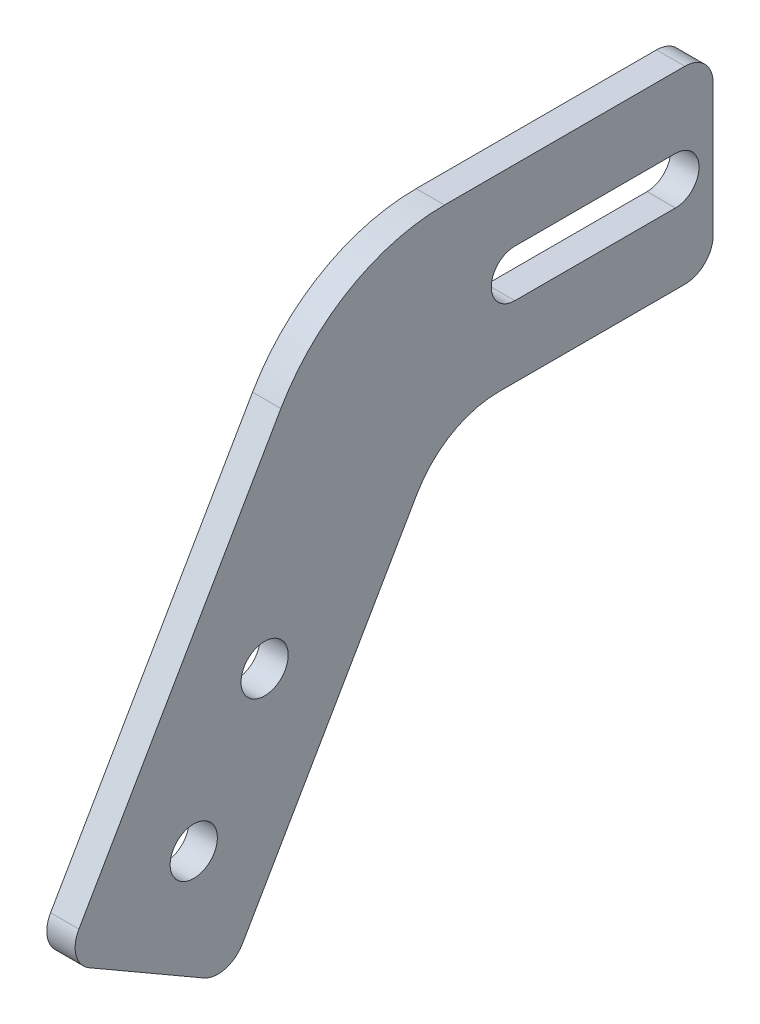
SolidWorks part; units mm, degrees
material "Thornel VCB-20 Carbon Cloth"
ref_plane "Front Plane" through (0, 0, 0) normal (0, 0, 1) x (1, 0, 0)
ref_plane "Top Plane" through (0, 0, 0) normal (0, 1, 0) x (1, 0, 0)
ref_plane "Right Plane" through (0, 0, 0) normal (1, 0, 0) x (0, 0, -1)
sketch "Sketch1" plane through (0, 0, 0) normal (1, 0, 0) x (0, 0, -1)
  line L7 (0, 0) -> (54.8406, 0) construction
  line L8 (0, 0) -> (-20, -34.641) construction
  line L9 (17.3205, 0) -> (40, 0)
  line L10 (40, 0) -> (40, 20)
  line L11 (40, 20) -> (11.547, 20)
  line L12 (-5.7735, 10) -> (-28.6603, -29.641)
  line L13 (8.6603, -5) -> (-11.3397, -39.641)
  line L14 (-8.6603, 5) -> (-28.6603, -29.641) construction
  line L15 (8.6603, -5) -> (-11.3397, -39.641) construction
  line L16 (0, 0) -> (19.0643, -11.0068) construction
  line L17 (-28.6603, -29.641) -> (-11.3397, -39.641)
  line L18 (40, 10) -> (-19.6071, 10) construction
  line L19 (0, 0) -> (0, 39.1739) construction
  line L20 (19, 12.5) -> (36, 12.5)
  line L21 (36, 7.5) -> (19, 7.5)
  arc A0 (8.6603, -5) -> (17.3205, 0) centre (17.3205, -10) cw
  arc A1 (-5.7735, 10) -> (11.547, 20) centre (11.547, 0) cw
  arc A2 (36, 7.5) -> (36, 12.5) centre (36, 10) ccw
  arc A3 (19, 12.5) -> (19, 7.5) centre (19, 10) ccw
  circle A4 centre (-15, -25.9808) radius 2.5
  circle A5 centre (-7.5, -12.9904) radius 2.5
  point P14 (11.547, 0)
  point P19 (0, 20)
  point P35 (19, 12.5)
  point P36 (36, 12.5)
  point P37 (36, 7.5)
  point P38 (19, 7.5)
  dimension "D7" = 10
  dimension "D8" = 20
  dimension "D9" = 5
  dimension "D10" = 5
  dimension "D13" = 5
  dimension "D14" = 5
  dimension "D1" = 120
  dimension "D2" = 10
  dimension "D4" = 20
  dimension "D5" = 40
  dimension "D6" = 40
  dimension "D11" = 4
  dimension "D12" = 17
  dimension "D15" = 10
  dimension "D16" = 15
  dimension "D3" = 10
extrude "Boss-Extrude1" add sketch "Sketch1" along normal blind 3
fillet "Fillet1" radius 3 4 edges at (1.5, -29.641, 28.6603) (1.5, -39.641, 11.3397) (1.5, 0, -40) (1.5, 20, -40)
